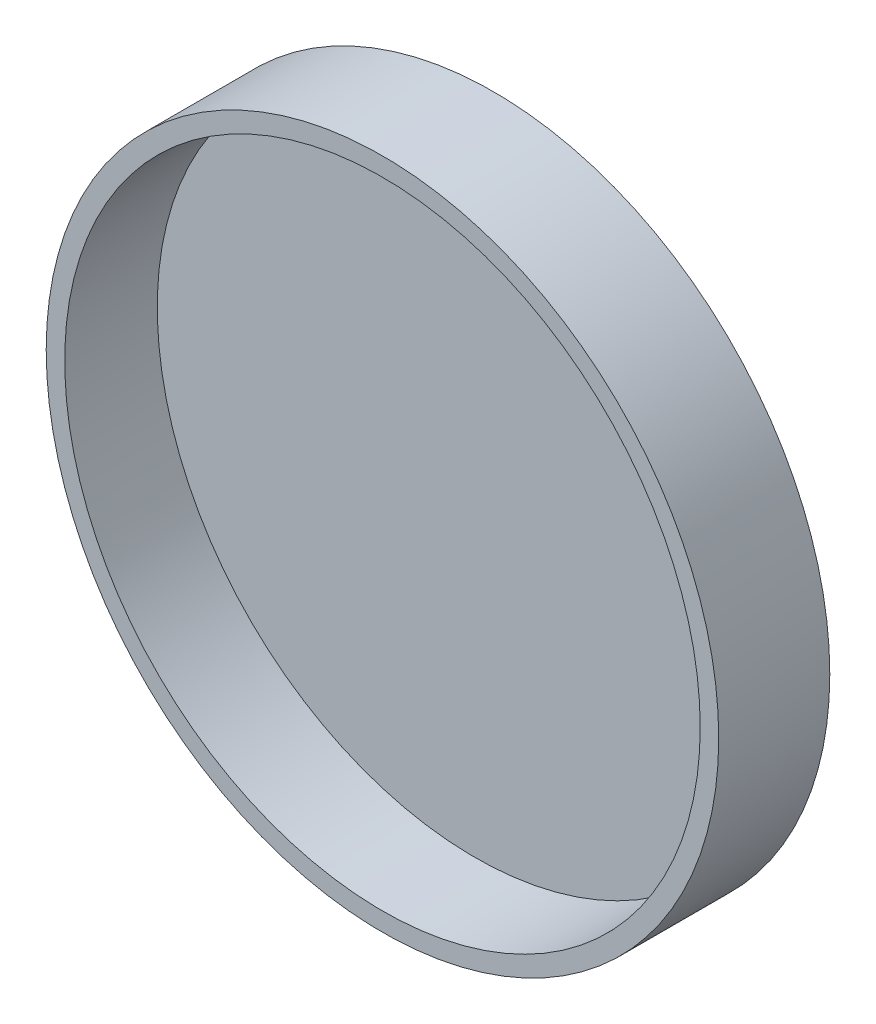
SolidWorks part; units mm, degrees
ref_plane "Front Plane" through (0, 0, 0) normal (0, 0, 1) x (1, 0, 0)
ref_plane "Top Plane" through (0, 0, 0) normal (0, 1, 0) x (1, 0, 0)
ref_plane "Right Plane" through (0, 0, 0) normal (1, 0, 0) x (0, 0, -1)
sketch "Sketch1" plane through (0, 0, 0) normal (0, 0, 1) x (1, 0, 0)
  circle A0 centre (0, 0) radius 54.5
  circle A1 centre (0, 0) radius 51.5
  dimension "D1" = 103
  dimension "D2" = 3
extrude "Boss-Extrude1" add sketch "Sketch1" along normal blind 15
sketch "Sketch2" plane through (0, 0, 0) normal (0, 0, -1) x (-1, 0, 0)
  circle A0 centre (0, 0) radius 54.5
extrude "Boss-Extrude2" add sketch "Sketch2" along normal blind 3
